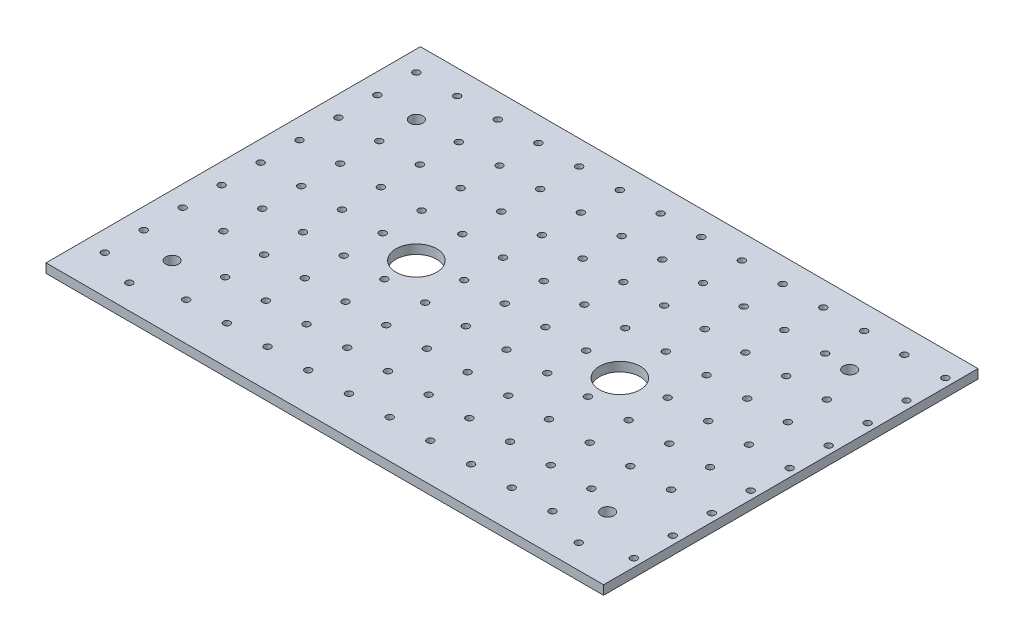
SolidWorks part; units mm, degrees
ref_plane "Front Plane" through (0, 0, 0) normal (0, 0, 1) x (1, 0, 0)
ref_plane "Top Plane" through (0, 0, 0) normal (0, 1, 0) x (1, 0, 0)
ref_plane "Right Plane" through (0, 0, 0) normal (1, 0, 0) x (0, 0, -1)
sketch "Sketch2" plane through (0, 0, 0) normal (0, 1, 0) x (1, 0, 0)
  line L0 (135.9382, 90) -> (-138.0618, 90) construction
  line L1 (-137, 92) -> (137, 92)
  line L2 (-137, 92) -> (-137, -92)
  line L3 (-137, -92) -> (137, -92)
  line L4 (137, 92) -> (137, -92)
  line L5 (-137, 92) -> (137, -92) construction
  line L6 (-137, -92) -> (137, 92) construction
  line L8 (135.9382, -90) -> (-138.0618, -90) construction
  circle A0 centre (-127, 80) radius 1.65
  circle A2 centre (-87, 80) radius 1.65
  circle A3 centre (-67, 80) radius 1.65
  circle A4 centre (-47, 80) radius 1.65
  circle A5 centre (-27, 80) radius 1.65
  circle A6 centre (-7, 80) radius 1.65
  circle A7 centre (13, 80) radius 1.65
  circle A8 centre (33, 80) radius 1.65
  circle A9 centre (53, 80) radius 1.65
  circle A10 centre (73, 80) radius 1.65
  circle A11 centre (93, 80) radius 1.65
  circle A13 centre (133, 80) radius 1.65
  circle A15 centre (-86.9854, 60.8454) radius 1.65
  circle A16 centre (-66.9854, 60.8454) radius 1.65
  circle A17 centre (-46.9854, 60.8454) radius 1.65
  circle A18 centre (-26.9854, 60.8454) radius 1.65
  circle A19 centre (-6.9854, 60.8454) radius 1.65
  circle A20 centre (13.0146, 60.8454) radius 1.65
  circle A21 centre (33.0146, 60.8454) radius 1.65
  circle A22 centre (53.0146, 60.8454) radius 1.65
  circle A23 centre (73.0146, 60.8454) radius 1.65
  circle A24 centre (93.0146, 60.8454) radius 1.65
  circle A26 centre (133.0146, 60.8454) radius 1.65
  circle A27 centre (-106.9709, 41.6908) radius 1.65
  circle A28 centre (-86.9709, 41.6908) radius 1.65
  circle A29 centre (-66.9709, 41.6908) radius 1.65
  circle A30 centre (-46.9709, 41.6908) radius 1.65
  circle A31 centre (-26.9709, 41.6908) radius 1.65
  circle A32 centre (-6.9709, 41.6908) radius 1.65
  circle A33 centre (13.0291, 41.6908) radius 1.65
  circle A34 centre (33.0291, 41.6908) radius 1.65
  circle A35 centre (53.0291, 41.6908) radius 1.65
  circle A36 centre (73.0291, 41.6908) radius 1.65
  circle A37 centre (93.0291, 41.6908) radius 1.65
  circle A38 centre (113.0291, 41.6908) radius 1.65
  circle A39 centre (133.0291, 41.6908) radius 1.65
  circle A40 centre (-106.9563, 22.5363) radius 1.65
  circle A41 centre (-86.9563, 22.5363) radius 1.65
  circle A42 centre (-66.9563, 22.5363) radius 1.65
  circle A43 centre (-46.9563, 22.5363) radius 1.65
  circle A44 centre (-26.9563, 22.5363) radius 1.65
  circle A45 centre (-6.9563, 22.5363) radius 1.65
  circle A46 centre (13.0437, 22.5363) radius 1.65
  circle A47 centre (33.0437, 22.5363) radius 1.65
  circle A48 centre (53.0437, 22.5363) radius 1.65
  circle A49 centre (73.0437, 22.5363) radius 1.65
  circle A50 centre (93.0437, 22.5363) radius 1.65
  circle A51 centre (113.0437, 22.5363) radius 1.65
  circle A52 centre (133.0437, 22.5363) radius 1.65
  circle A53 centre (-106.9418, 3.3817) radius 1.65
  circle A54 centre (-86.9418, 3.3817) radius 1.65
  circle A55 centre (-66.9418, 3.3817) radius 1.65
  circle A57 centre (-26.9418, 3.3817) radius 1.65
  circle A58 centre (-6.9418, 3.3817) radius 1.65
  circle A59 centre (13.0582, 3.3817) radius 1.65
  circle A60 centre (33.0582, 3.3817) radius 1.65
  circle A62 centre (73.0582, 3.3817) radius 1.65
  circle A63 centre (93.0582, 3.3817) radius 1.65
  circle A64 centre (113.0582, 3.3817) radius 1.65
  circle A65 centre (133.0582, 3.3817) radius 1.65
  circle A66 centre (-106.9272, -15.7729) radius 1.65
  circle A67 centre (-86.9272, -15.7729) radius 1.65
  circle A68 centre (-66.9272, -15.7729) radius 1.65
  circle A69 centre (-46.9272, -15.7729) radius 1.65
  circle A70 centre (-26.9272, -15.7729) radius 1.65
  circle A71 centre (-6.9272, -15.7729) radius 1.65
  circle A72 centre (13.0728, -15.7729) radius 1.65
  circle A73 centre (33.0728, -15.7729) radius 1.65
  circle A74 centre (53.0728, -15.7729) radius 1.65
  circle A75 centre (73.0728, -15.7729) radius 1.65
  circle A76 centre (93.0728, -15.7729) radius 1.65
  circle A77 centre (113.0728, -15.7729) radius 1.65
  circle A78 centre (133.0728, -15.7729) radius 1.65
  circle A79 centre (-106.9126, -34.9275) radius 1.65
  circle A80 centre (-86.9126, -34.9275) radius 1.65
  circle A81 centre (-66.9126, -34.9275) radius 1.65
  circle A82 centre (-46.9126, -34.9275) radius 1.65
  circle A83 centre (-26.9126, -34.9275) radius 1.65
  circle A84 centre (-6.9126, -34.9275) radius 1.65
  circle A85 centre (13.0874, -34.9275) radius 1.65
  circle A86 centre (33.0874, -34.9275) radius 1.65
  circle A87 centre (53.0874, -34.9275) radius 1.65
  circle A88 centre (73.0874, -34.9275) radius 1.65
  circle A89 centre (93.0874, -34.9275) radius 1.65
  circle A90 centre (113.0874, -34.9275) radius 1.65
  circle A91 centre (133.0874, -34.9275) radius 1.65
  circle A93 centre (-86.8981, -54.082) radius 1.65
  circle A94 centre (-66.8981, -54.082) radius 1.65
  circle A95 centre (-46.8981, -54.082) radius 1.65
  circle A96 centre (-26.8981, -54.082) radius 1.65
  circle A97 centre (-6.8981, -54.082) radius 1.65
  circle A98 centre (13.1019, -54.082) radius 1.65
  circle A99 centre (33.1019, -54.082) radius 1.65
  circle A100 centre (53.1019, -54.082) radius 1.65
  circle A101 centre (73.1019, -54.082) radius 1.65
  circle A102 centre (93.1019, -54.082) radius 1.65
  circle A104 centre (133.1019, -54.082) radius 1.65
  circle A106 centre (-86.8835, -73.2366) radius 1.65
  circle A107 centre (-66.8835, -73.2366) radius 1.65
  circle A108 centre (-46.8835, -73.2366) radius 1.65
  circle A109 centre (-26.8835, -73.2366) radius 1.65
  circle A110 centre (-6.8835, -73.2366) radius 1.65
  circle A111 centre (13.1165, -73.2366) radius 1.65
  circle A112 centre (33.1165, -73.2366) radius 1.65
  circle A113 centre (53.1165, -73.2366) radius 1.65
  circle A114 centre (73.1165, -73.2366) radius 1.65
  circle A115 centre (93.1165, -73.2366) radius 1.65
  circle A117 centre (133.1165, -73.2366) radius 1.65
  circle A118 centre (-126.9854, 60.8454) radius 1.65
  circle A119 centre (-126.9709, 41.6908) radius 1.65
  circle A120 centre (-126.9563, 22.5363) radius 1.65
  circle A121 centre (-126.9418, 3.3817) radius 1.65
  circle A122 centre (-126.9272, -15.7729) radius 1.65
  circle A123 centre (-126.9126, -34.9275) radius 1.65
  circle A124 centre (-126.8981, -54.082) radius 1.65
  circle A125 centre (-126.8835, -73.2366) radius 1.65
  circle A126 centre (-107, 60) radius 3.15
  circle A127 centre (-107, 80) radius 1.65 [skipped]
  circle A128 centre (-107, -60) radius 3.15
  circle A129 centre (-106.8835, -73.2366) radius 1.65 [skipped]
  circle A130 centre (107, -60) radius 3.15
  circle A131 centre (113.1165, -73.2366) radius 1.65 [skipped]
  circle A132 centre (105.9382, 60) radius 3.15
  circle A133 centre (113, 80) radius 1.65 [skipped]
  circle A134 centre (53, 0) radius 10
  circle A135 centre (53.0582, 3.3817) radius 1.65 [skipped]
  circle A136 centre (-47, 0) radius 10
  circle A137 centre (-46.9418, 3.3817) radius 1.65 [skipped]
  circle A138 centre (113.1019, -54.082) radius 1.65 [skipped]
  circle A139 centre (113, -80.1922) radius 1.65
  circle A140 centre (113.0146, 60.8454) radius 1.65 [skipped]
  circle A141 centre (113, 79.8078) radius 1.65
  circle A142 centre (-106.8981, -54.082) radius 1.65 [skipped]
  circle A143 centre (-108.0618, -80) radius 1.65
  circle A144 centre (-106.9854, 60.8454) radius 1.65 [skipped]
  circle A145 centre (-107, 80) radius 1.65
  point P0 (0, 0)
  dimension "D5" = 3.3
  dimension "D8" = 6.3
  dimension "D10" = 30
  dimension "D13" = 6.3
  dimension "D16" = 6.3
  dimension "D17" = 6.3
  dimension "D19" = 20
  dimension "D20" = 20
  dimension "D1" = 274
  dimension "D2" = 184
  dimension "D3" = 10
  dimension "D4" = 10
  dimension "D9" = 30
  dimension "D11" = 30
  dimension "D12" = 30
  dimension "D14" = 30
  dimension "D15" = 30
  dimension "D18" = 30
  dimension "D21" = 20
  dimension "D22" = 20
  dimension "D23" = 20
  dimension "D6" = 14
  dimension "D7" = 9
extrude "Boss-Extrude1" add sketch "Sketch2" along normal mid plane 4.5
